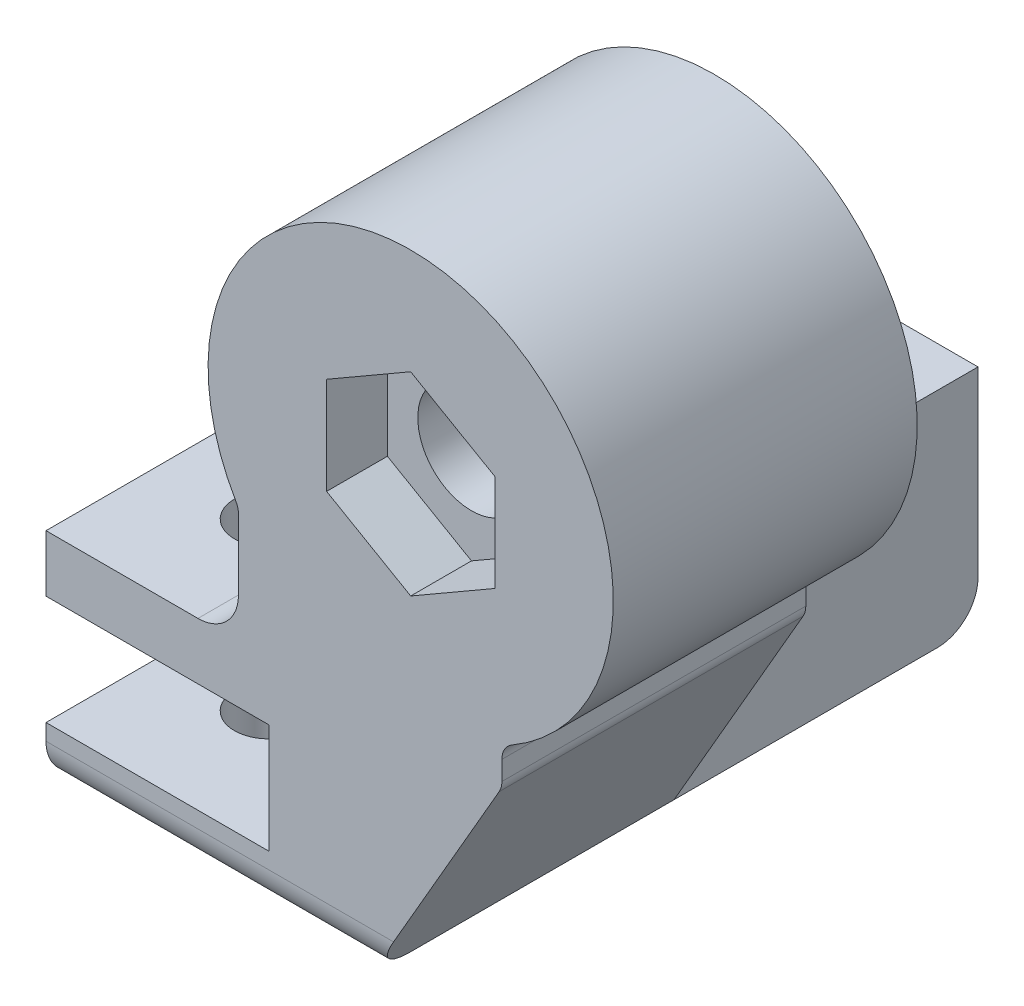
SolidWorks part; units mm, degrees
ref_plane "前视基准面" through (0, 0, 0) normal (0, 0, 1) x (1, 0, 0)
ref_plane "上视基准面" through (0, 0, 0) normal (0, 1, 0) x (1, 0, 0)
ref_plane "右视基准面" through (0, 0, 0) normal (1, 0, 0) x (0, 0, -1)
other "Configuration Table"
sketch "草图2" plane through (0, 0, 0) normal (0, 0, 1) x (1, 0, 0)
  line L0 (0, 0) -> (0, 2.8)
  line L1 (0, 2.8) -> (11, 2.8)
  line L2 (11, 2.8) -> (11, 8.2)
  line L3 (11, 8.2) -> (0, 8.2)
  line L4 (0, 8.2) -> (0, 11)
  line L5 (0, 11) -> (16, 11)
  line L6 (16, 11) -> (16, 0)
  line L7 (16, 0) -> (0, 0)
  point P4 (8, 0)
  dimension "D1" = 2.8
  dimension "D2" = 2.8
  dimension "D3" = 5.4
  dimension "D4" = 11
  dimension "D5" = 16
extrude "凸台-拉伸1" add sketch "草图2" against normal blind 30
sketch "草图3" plane through (0, 0, 0) normal (0, 0, 1) x (1, 0, 0)
  line L0 (9.5, 11) -> (9.5, 16.7322)
  line L1 (16, 11) -> (0, 11) construction
  line L2 (22.5, 11.2583) -> (22.5, 13.0697)
  line L3 (22.5, 11.2583) -> (16, 0)
  line L4 (16, 0) -> (16, 11)
  line L5 (16, 11) -> (9.5, 11)
  line L6 (0, 11) -> (0, 8.2) construction
  line L7 (0, 0) -> (16, 0) construction
  arc A0 (22.5, 13.0697) -> (9.5, 16.7322) centre (18, 22) ccw
  circle A1 centre (18, 22) radius 2.65
  point P18 (17.6177, 22)
  dimension "D1" = 10
  dimension "D7" = 5.3
  dimension "D2" = 11
  dimension "D3" = 18
  dimension "D4" = 9.5
  dimension "D5" = 22.5
  dimension "D6" = 120
extrude "凸台-拉伸2" add sketch "草图3" against normal blind 15
sketch "草图4" plane through (0, 0, -15) normal (0, 0, -1) x (-1, 0, 0)
  circle A0 centre (-18, 22) radius 5
  dimension "D1" = 10
extrude "切除-拉伸1" cut sketch "草图4" against normal blind 5
sketch "草图5" plane through (0, 0, 0) normal (0, 0, 1) x (1, 0, 0)
  line L0 (18, 22) -> (18, 28.9192) construction
  line L1 (18, 26.792) -> (13.85, 24.396)
  line L2 (13.85, 24.396) -> (13.85, 19.604)
  line L3 (13.85, 19.604) -> (18, 17.208)
  line L4 (18, 17.208) -> (22.15, 19.604)
  line L5 (22.15, 19.604) -> (22.15, 24.396)
  line L6 (22.15, 24.396) -> (18, 26.792)
  circle A0 centre (18, 22) radius 4.15 construction
  dimension "D1" = 8.3
extrude "切除-拉伸2" cut sketch "草图5" against normal blind 3
sketch "草图6" plane through (0, 11, 0) normal (0, 1, 0) x (1, 0, 0)
  line L0 (5, -4.659) -> (5, 34.9473) construction
  line L1 (0, 30) -> (0, 0) construction
  line L2 (16, 30) -> (0, 30) construction
  line L3 (9.5, 0) -> (0, 0) construction
  circle A0 centre (5, 6) radius 1.7
  circle A1 centre (5, 24) radius 1.7
  dimension "D2" = 3.4
  dimension "D3" = 3.4
  dimension "D1" = 5
  dimension "D4" = 6
  dimension "D5" = 6
extrude "切除-拉伸3" cut sketch "草图6" against normal through all and the other way through all
fillet "圆角1" radius 2 1 edges at (9.5, 11, -7.5)
fillet "圆角2" radius 1 1 edges at (9.5, 16.7322, -7.5)
fillet "圆角3" radius 1 2 edges at (22.5, 11.2583, -7.5) (22.5, 13.0697, -7.5)
fillet "圆角5" radius 2 2 edges at (8, 0, 0) (8, 0, -30)
